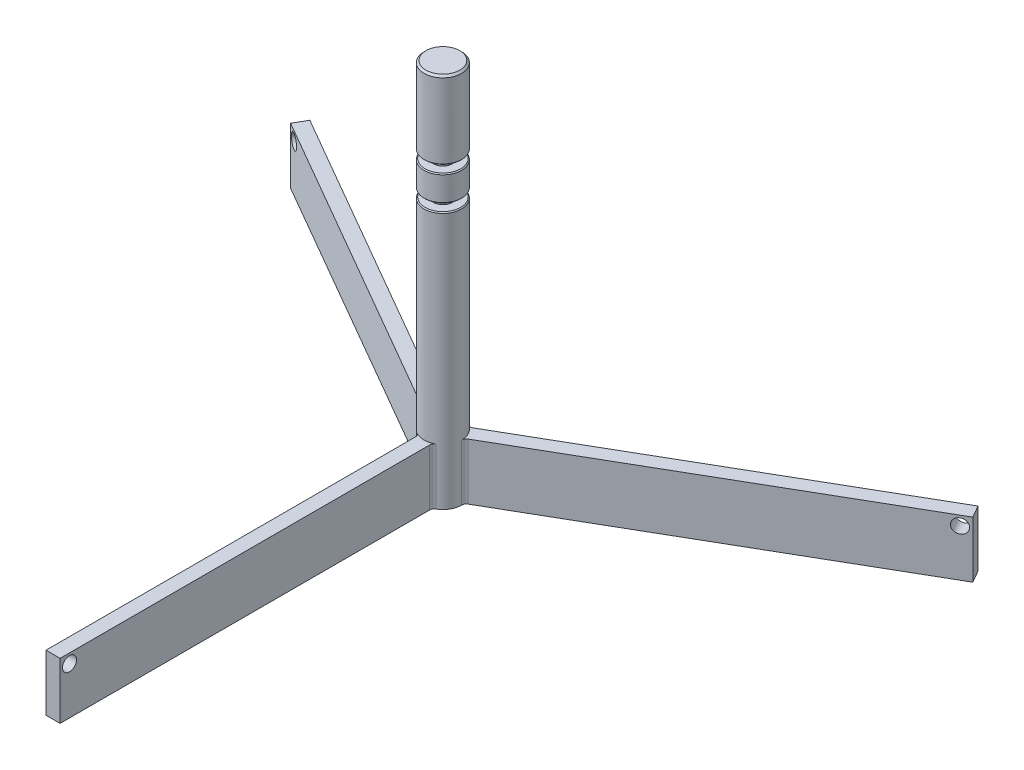
SolidWorks part; units mm, degrees
ref_plane "Front" through (0, 0, 0) normal (0, 0, 1) x (1, 0, 0)
ref_plane "Top" through (0, 0, 0) normal (0, 1, 0) x (1, 0, 0)
ref_plane "Right" through (0, 0, 0) normal (1, 0, 0) x (0, 0, -1)
sketch "Sketch5" plane through (0, 0, 0) normal (0, 0, 1) x (1, 0, 0)
  line L0 (0, 112.3855) -> (0, -102.7942) construction
  line L1 (12.7, 173.99) -> (6.35, 173.99)
  line L2 (0, 0) -> (12.7, 0)
  line L3 (0, 0) -> (0, 254)
  line L4 (0, 254) -> (12.7, 254)
  line L5 (12.7, 0) -> (12.7, 173.99)
  line L6 (6.35, 173.99) -> (6.35, 179.07)
  line L7 (6.35, 179.07) -> (12.7, 179.07)
  line L8 (12.7, 196.596) -> (6.35, 196.596)
  line L9 (6.35, 196.596) -> (6.35, 201.676)
  line L10 (6.35, 201.676) -> (12.7, 201.676)
  line L11 (12.7, 179.07) -> (12.7, 196.596)
  line L12 (12.7, 201.676) -> (12.7, 254)
  dimension "D1" = 254
  dimension "D2" = 12.7
  dimension "D3" = 6.35
  dimension "D4" = 5.08
  dimension "D5" = 74.93
  dimension "D6" = 52.324
revolve "Base-Revolve" add sketch "Sketch5" angle 360 about L0
sketch "Sketch6" plane through (0, 0, 0) normal (0, 0, 1) x (1, 0, 0)
  line L1 (-4.7625, 0) -> (4.7625, 0)
  line L2 (-4.7625, 0) -> (-4.7625, 38.1)
  line L3 (-4.7625, 38.1) -> (4.7625, 38.1)
  line L4 (4.7625, 0) -> (4.7625, 38.1)
  point P4 (0, 0)
  dimension "D1" = 38.1
  dimension "D2" = 9.525
extrude "Boss-Extrude2" add sketch "Sketch6" along normal blind 263.525
sketch "Sketch7" plane through (4.7625, 0, 0) normal (1, 0, 0) x (0, 0, -1)
  line L0 (-263.525, 0) -> (-263.525, 38.1) construction
  line L1 (-263.525, 38.1) -> (-11.7732, 38.1) construction
  circle A0 centre (-257.175, 31.75) radius 4.7625
  dimension "D1" = 9.525
  dimension "D2" = 6.35
  dimension "D3" = 6.35
extrude "Cut-Extrude2" cut sketch "Sketch7" against normal through all
fillet "Fillet2" radius 3.175 2 edges at (-4.7625, 19.05, 11.7732) (4.7625, 19.05, 11.7732)
pattern_circular "CirPattern2" count 3 over 360 about axis through (0, 0, 0) along (0, 1, 0) of "Fillet2", "Cut-Extrude2", "Boss-Extrude2"
chamfer "Chamfer5" distance 0.635 angle 45 4 edges at (0, 179.07, 12.7) (0, 196.596, 12.7) (0, 201.676, 12.7) (0, 173.99, 12.7)
chamfer "Chamfer6" distance 1.27 angle 45 1 edges at (0, 254, 12.7)
